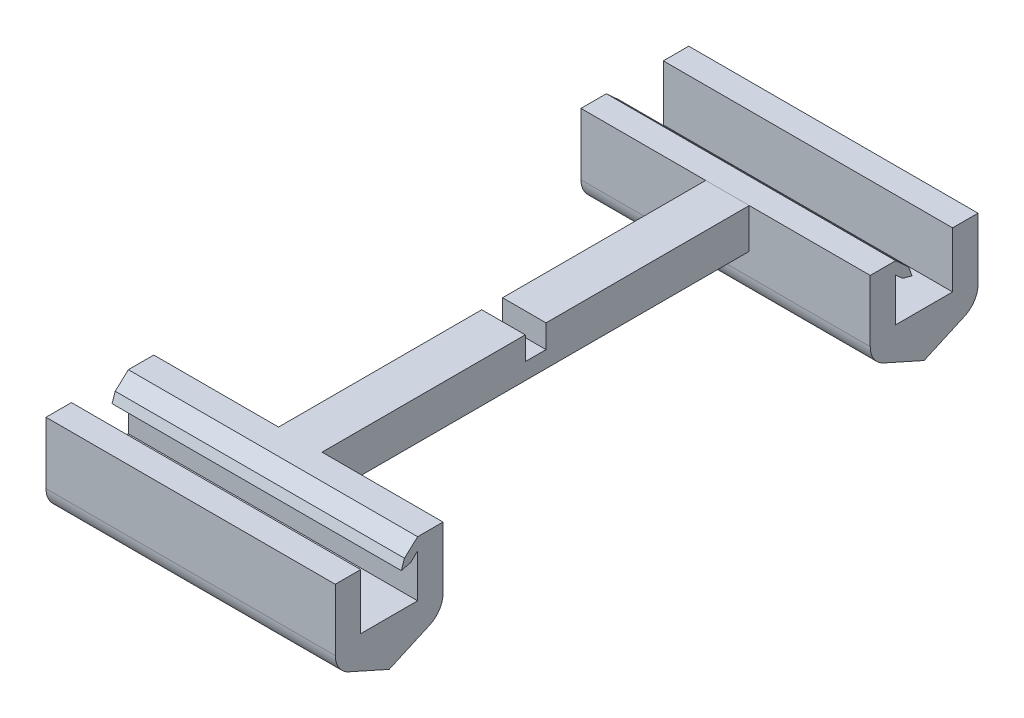
SolidWorks part; units mm, degrees
ref_plane "Front Plane" through (0, 0, 0) normal (0, 0, 1) x (1, 0, 0)
ref_plane "Top Plane" through (0, 0, 0) normal (0, 1, 0) x (1, 0, 0)
ref_plane "Right Plane" through (0, 0, 0) normal (1, 0, 0) x (0, 0, -1)
sketch "Sketch1" plane through (0, 0, 0) normal (1, 0, 0) x (0, 0, -1)
  line L0 (0, 0) -> (0, 50000) construction
  line L1 (10.4935, -0.4434) -> (10.4935, 0.1001) construction
  line L2 (11.2106, -0.8313) -> (10.935, -0.5778) construction
  line L3 (11.0704, -0.4306) -> (10.7996, -0.725) construction
  line L4 (10.7996, -0.725) -> (10.4935, -0.4434)
  line L5 (11.2106, -0.8313) -> (10.7996, -0.725)
  line L6 (11.0704, -0.4306) -> (11.2106, -0.8313)
  line L7 (10.4935, 0.1001) -> (11.0704, -0.4306)
  line L8 (9.3777, 0.1001) -> (9.3777, -2.6134)
  line L9 (9.969, -3.5261) -> (11.7435, -4.3205)
  line L10 (12.9935, 0.1001) -> (14.1094, 0.1001)
  line L11 (12.9935, -2.3373) -> (12.9935, 0.1001)
  line L12 (-10.4935, 0.1001) -> (-9.3777, 0.1001)
  line L13 (-10.4935, -2.3373) -> (-10.4935, -0.4434)
  line L14 (-12.9935, -2.3373) -> (-10.4935, -2.3373)
  line L15 (-13.518, -3.5261) -> (-11.7435, -4.3205)
  line L16 (-14.1094, 0.1001) -> (-14.1094, -2.6134)
  line L17 (-12.9935, -2.3373) -> (-12.9935, 0.1001)
  line L18 (-12.9935, 0.1001) -> (-14.1094, 0.1001)
  line L19 (-9.969, -3.5261) -> (-11.7435, -4.3205)
  line L20 (-9.3777, 0.1001) -> (-9.3777, -2.6134)
  line L21 (-10.4935, 0.1001) -> (-11.0704, -0.4306)
  line L22 (-11.0704, -0.4306) -> (-11.2106, -0.8313)
  line L23 (-11.2106, -0.8313) -> (-10.7996, -0.725)
  line L24 (-10.7996, -0.725) -> (-10.4935, -0.4434)
  line L25 (-11.0704, -0.4306) -> (-10.7996, -0.725) construction
  line L26 (-11.2106, -0.8313) -> (-10.935, -0.5778) construction
  line L27 (-10.4935, -0.4434) -> (-10.4935, 0.1001) construction
  line L28 (14.1094, 0.1001) -> (14.1094, -2.6134)
  line L29 (13.518, -3.5261) -> (11.7435, -4.3205)
  line L30 (12.9935, -2.3373) -> (10.4935, -2.3373)
  line L31 (10.4935, -2.3373) -> (10.4935, -0.4434)
  line L32 (10.4935, 0.1001) -> (9.3777, 0.1001)
  arc A0 (-9.969, -3.5261) -> (-9.3777, -2.6134) centre (-10.3777, -2.6134) ccw
  arc A1 (-13.518, -3.5261) -> (-14.1094, -2.6134) centre (-13.1094, -2.6134) cw
  arc A2 (13.518, -3.5261) -> (14.1094, -2.6134) centre (13.1094, -2.6134) ccw
  arc A3 (9.969, -3.5261) -> (9.3777, -2.6134) centre (10.3777, -2.6134) cw
  point P3 (0, 0)
  point P27 (-9.3777, -3.2613)
  point P35 (0, 0)
  point P42 (9.3777, -3.2613)
  point P46 (0, 0)
  point P47 (0, 0)
  dimension "D3" = 1
  dimension "D1" = 12.9935
  dimension "D2" = 1.1159
  dimension "D4" = 0.4
  dimension "D5" = 2.7135
  dimension "D6" = 1.9442
  dimension "D7" = 1.9442
  dimension "D8" = 2.7135
  dimension "D9" = 1.1159
extrude "Boss-Extrude1" add sketch "Sketch1" along normal blind 12.7
sketch "Sketch2" plane through (0, 0, -9.3777) normal (0, 0, 1) x (1, 0, 0)
  line L1 (5.4781, 0.1001) -> (7.3878, 0.1001)
  line L2 (5.4781, 0.1001) -> (5.4781, -1.6416)
  line L3 (5.4781, -1.6416) -> (7.3878, -1.6416) construction
  line L4 (7.3878, 0.1001) -> (7.3878, -1.6416)
  line L5 (5.4781, -1.6416) -> (6.433, -2.5964)
  line L6 (6.433, -2.5964) -> (7.3878, -1.6416)
  line L8 (12.7, 0.1001) -> (0, 0.1001) construction
extrude "Boss-Extrude2" add sketch "Sketch2" along normal up to next
sketch "Sketch3" plane through (5.4781, 0, 0) normal (-1, 0, 0) x (0, 0, 1)
  line L0 (0, 0) -> (0, -50000) construction
  line L1 (9.3777, 0.1001) -> (-9.3777, 0.1001) construction
  line L2 (0.456, -0.9172) -> (0.456, 0.1001)
  line L3 (-0.456, -0.9172) -> (-0.456, 0.1001)
  line L4 (-0.456, 0.1001) -> (0.456, 0.1001)
  line L5 (0.456, -0.9172) -> (-0.456, -0.9172)
  point P4 (0, 0.1001)
  dimension "D1" = 0.912
extrude "Cut-Extrude1" cut sketch "Sketch3" against normal up to next (1.9097 mm away)
